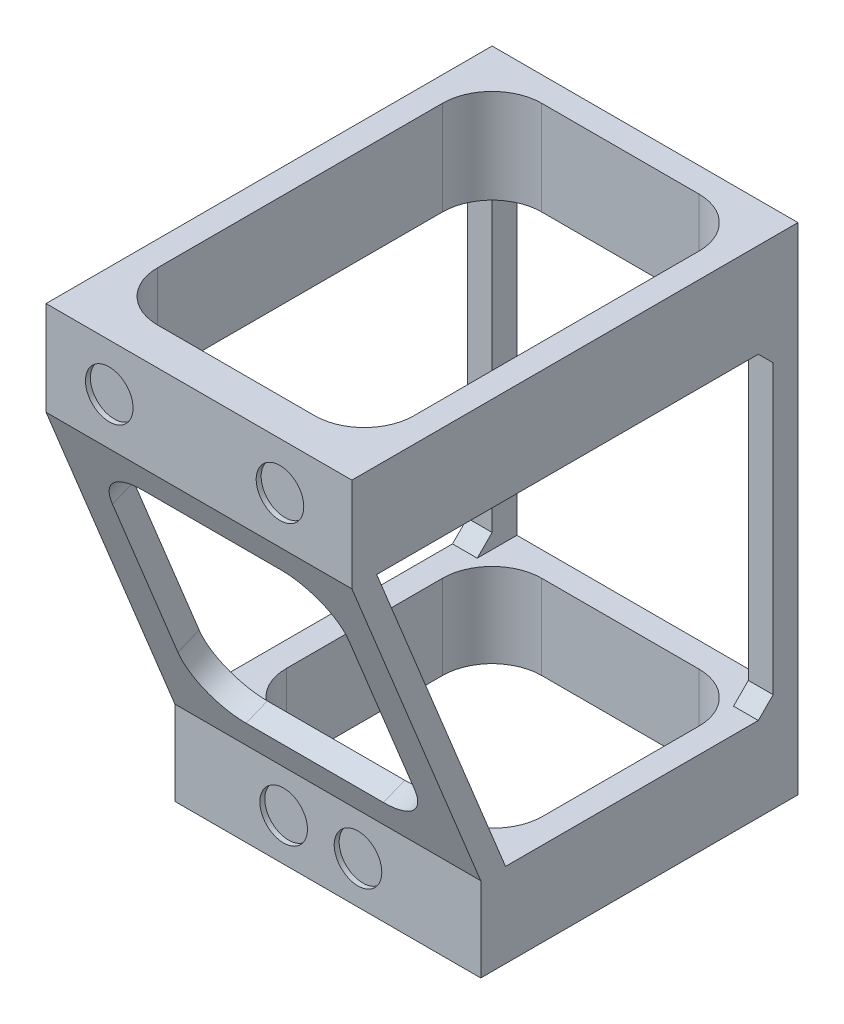
SolidWorks part; units mm, degrees
ref_plane "Front Plane" through (0, 0, 0) normal (1, 0, 0) x (0, 1, 0)
ref_plane "Top Plane" through (0, 0, 0) normal (0, 0, 1) x (0, 1, 0)
ref_plane "Right Plane" through (0, 0, 0) normal (0, 1, 0) x (-1, 0, 0)
sketch "Sketch3" plane through (0, 0, 0) normal (1, 0, 0) x (0, 1, 0)
  line L0 (0, 5) -> (0, 0)
  line L1 (0, 5) -> (17, 5)
  line L2 (17, 5) -> (81, 31)
  line L3 (81, 31) -> (100, 31)
  line L4 (0, 0) -> (17, 0)
  line L5 (17, 0) -> (81, 26)
  line L6 (81, 26) -> (100, 26)
  line L7 (100, 26) -> (100, 31)
  dimension "D1" = 100
  dimension "D2" = 26
  dimension "D3" = 17
  dimension "D4" = 19
  dimension "D5" = 5
extrude "Boss-Extrude1" add sketch "Sketch3" along normal blind 58.71
sketch "Sketch4" plane through (0, 0, 31) normal (0, 0, 1) x (1, 0, 0)
  line L0 (29.27, 23.6763) -> (29.27, 76.7509) construction
  line L1 (58.71, 100) -> (0, 100) construction
  line L7 (0, 81) -> (0, 17) construction
  line L8 (0, 100) -> (0, 81) construction
  circle A0 centre (12.75, 90.5) radius 4.8
  circle A1 centre (47.2, 90.5) radius 4.8
  dimension "D2" = 9.6
  dimension "D3" = 9.6
  dimension "D1" = 9.5
  dimension "D4" = 29.27
  dimension "D5" = 12.75
  dimension "D6" = 16.52
  dimension "D7" = 17.93
extrude "Cut-Extrude1" cut sketch "Sketch4" against normal blind 1
sketch "Sketch5" plane through (0, 0, 5) normal (0, 0, 1) x (1, 0, 0)
  line L0 (29.355, 100) -> (29.355, 58.2947) construction
  line L1 (58.71, 100) -> (0, 100) construction
  line L2 (58.71, 0) -> (0, 0) construction
  line L3 (0, 17) -> (0, 0) construction
  circle A0 centre (21.94, 8.5) radius 4.8
  circle A1 centre (36.94, 8.5) radius 4.8
  dimension "D4" = 9.6
  dimension "D5" = 9.6
  dimension "D1" = 15
  dimension "D2" = 21.94
  dimension "D3" = 8.5
extrude "Cut-Extrude2" cut sketch "Sketch5" against normal blind 1
sketch "Sketch6" plane through (58.71, 0, 0) normal (1, 0, 0) x (0, 1, 0)
  line L0 (81, 26) -> (81, 0)
  line L1 (81, 0) -> (100, 0)
  line L2 (100, 0) -> (100, 26)
  line L3 (81, 26) -> (100, 26)
  line L4 (81, 26) -> (100, 26) construction
extrude "Boss-Extrude3" add sketch "Sketch6" against normal up to surface (58.71 mm away) up to face at (0, 49.5, 15.5)
sketch "Sketch7" plane through (0, 0, 0) normal (0, 0, -1) x (1, 0, 0)
  line L1 (0, 0) -> (58.71, 0)
  line L2 (0, 0) -> (0, -17)
  line L3 (0, -17) -> (58.71, -17)
  line L4 (58.71, 0) -> (58.71, -17)
  line L5 (0, -81) -> (58.71, -81)
  line L6 (0, -81) -> (0, -100)
  line L7 (0, -100) -> (58.71, -100)
  line L8 (58.71, -81) -> (58.71, -100)
extrude "Boss-Extrude4" add sketch "Sketch7" along normal blind 59
sketch "Sketch8" plane through (58.71, 0, 0) normal (1, 0, 0) x (0, 1, 0)
  line L0 (100, 31) -> (81, 31) construction
  line L1 (100, -59) -> (100, 31) construction
  line L2 (100, -59) -> (81, -59) construction
  line L3 (81, 26) -> (81, -59) construction
  line L4 (17, -59) -> (0, -59) construction
  line L5 (0, 5) -> (0, -59) construction
  line L6 (17, -59) -> (17, 0) construction
  line L7 (17, 0) -> (81, 26) construction
  line L8 (81, 31) -> (17, 5) construction
  line L9 (17, 5) -> (0, 5) construction
  line L10 (100, 31) -> (81, 31)
  line L11 (100, -59) -> (100, 31)
  line L12 (100, -59) -> (81, -59)
  line L13 (81, 26) -> (81, -59)
  line L14 (17, -59) -> (0, -59)
  line L15 (0, 5) -> (0, -59)
  line L16 (17, -59) -> (17, 0)
  line L17 (17, 0) -> (81, 26)
  line L18 (81, 31) -> (17, 5)
  line L19 (17, 5) -> (0, 5)
extrude "Boss-Extrude5" add sketch "Sketch8" along normal blind 3
sketch "Sketch9" plane through (0, 0, 0) normal (0, -1, 0) x (1, 0, 0)
  line L0 (61.71, 5) -> (0, 5) construction
  line L1 (15, -2.5) -> (46.71, -2.5)
  line L2 (5, -12.5) -> (5, -44)
  line L3 (15, -54) -> (46.71, -54)
  line L4 (56.71, -12.5) -> (56.71, -44)
  line L5 (61.71, -59) -> (0, -59) construction
  line L6 (0, 5) -> (0, -59) construction
  line L7 (61.71, 5) -> (61.71, -59) construction
  arc A0 (5, -44) -> (15, -54) centre (15, -44) ccw
  arc A1 (46.71, -54) -> (56.71, -44) centre (46.71, -44) ccw
  arc A2 (46.71, -2.5) -> (56.71, -12.5) centre (46.71, -12.5) cw
  arc A3 (15, -2.5) -> (5, -12.5) centre (15, -12.5) ccw
  dimension "D5" = 10
  dimension "D1" = 7.5
  dimension "D2" = 5
  dimension "D3" = 5
  dimension "D4" = 5
extrude "Cut-Extrude3" cut sketch "Sketch9" against normal up to surface (17 mm away) up to face at (30.855, 17, -29.5)
sketch "Sketch10" plane through (0, 100, 0) normal (0, 1, 0) x (-1, 0, 0)
  line L0 (-61.71, 31) -> (0, 31) construction
  line L1 (-46.71, 23.5) -> (-15, 23.5)
  line L2 (-56.71, 13.5) -> (-56.71, -44)
  line L3 (-46.71, -54) -> (-15, -54)
  line L4 (-5, 13.5) -> (-5, -44)
  line L5 (0, -59) -> (-61.71, -59) construction
  line L6 (-61.71, -59) -> (-61.71, 31) construction
  line L7 (0, -59) -> (0, 31) construction
  arc A0 (-15, -54) -> (-5, -44) centre (-15, -44) ccw
  arc A1 (-56.71, -44) -> (-46.71, -54) centre (-46.71, -44) ccw
  arc A2 (-15, 23.5) -> (-5, 13.5) centre (-15, 13.5) cw
  arc A3 (-46.71, 23.5) -> (-56.71, 13.5) centre (-46.71, 13.5) ccw
  dimension "D5" = 10
  dimension "D1" = 7.5
  dimension "D2" = 5
  dimension "D3" = 5
  dimension "D4" = 5
extrude "Cut-Extrude4" cut sketch "Sketch10" against normal up to surface (19 mm away) up to face at (30.855, 81, -16.5)
sketch "Sketch11" plane through (0, 0.6647, -1.6362) normal (0, -0.3764, 0.9265) x (1, 0, 0)
  line L0 (61.71, 86.7115) -> (0, 86.7115) construction
  line L1 (17, 79.7115) -> (44.71, 79.7115)
  line L2 (7, 69.7115) -> (7, 34.6318)
  line L3 (17, 24.6318) -> (44.71, 24.6318)
  line L4 (54.71, 69.7115) -> (54.71, 34.6318)
  line L5 (61.71, 17.6318) -> (0, 17.6318) construction
  line L6 (0, 86.7115) -> (0, 17.6318) construction
  line L7 (61.71, 86.7115) -> (61.71, 17.6318) construction
  arc A0 (44.71, 24.6318) -> (54.71, 34.6318) centre (44.71, 34.6318) ccw
  arc A1 (44.71, 79.7115) -> (54.71, 69.7115) centre (44.71, 69.7115) cw
  arc A2 (7, 34.6318) -> (17, 24.6318) centre (17, 34.6318) ccw
  arc A3 (17, 79.7115) -> (7, 69.7115) centre (17, 69.7115) ccw
  dimension "D5" = 10
  dimension "D1" = 7
  dimension "D2" = 7
  dimension "D3" = 7
  dimension "D4" = 7
extrude "Cut-Extrude5" cut sketch "Sketch11" against normal up to surface (4.6323 mm away) up to face at (30.855, 49, 13)
sketch "Sketch12" plane through (0, 0, 0) normal (0, -1, 0) x (1, 0, 0)
  line L0 (5, -12.5) -> (5, -44) construction
  line L1 (0, -59) -> (5, -59)
  line L2 (0, -59) -> (0, -54)
  line L3 (0, -54) -> (5, -54)
  line L4 (5, -59) -> (5, -54)
  line L5 (61.71, -59) -> (56.71, -59)
  line L6 (61.71, -59) -> (61.71, -54)
  line L7 (61.71, -54) -> (56.71, -54)
  line L8 (56.71, -59) -> (56.71, -54)
  line L9 (15, -54) -> (46.71, -54) construction
  line L10 (56.71, -44) -> (56.71, -12.5) construction
extrude "Boss-Extrude6" add sketch "Sketch12" against normal blind 100
chamfer "Chamfer1" distance 3 angle 45 4 edges at (59.21, 17, -54) (2.5, 17, -54) (2.5, 81, -54) (59.21, 81, -54)
